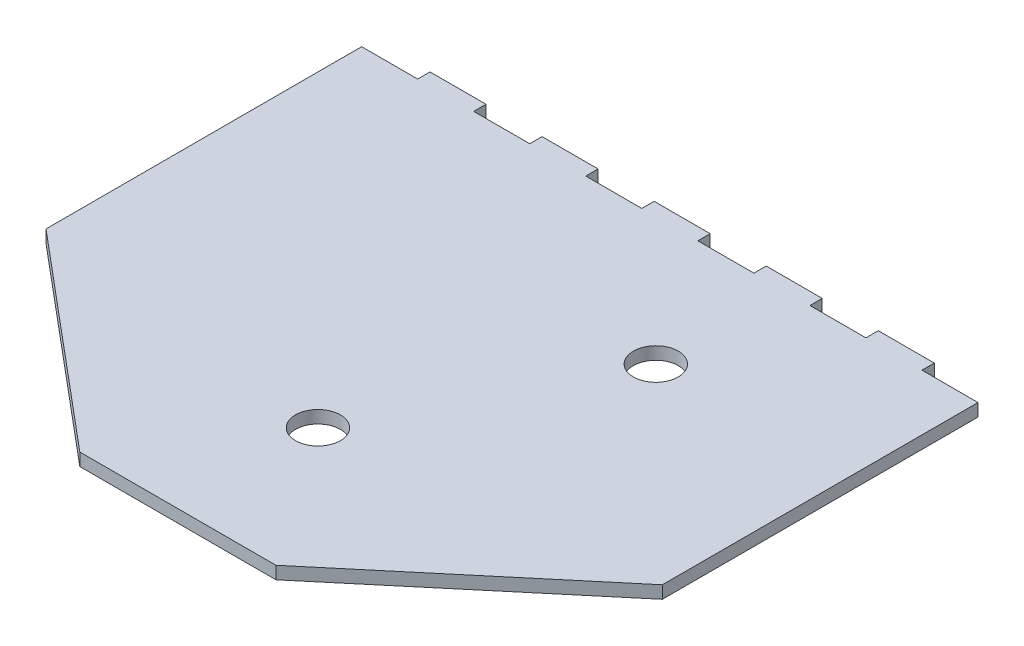
SolidWorks part; units mm, degrees
ref_plane "Front Plane" through (0, 0, 0) normal (0, 0, 1) x (1, 0, 0)
ref_plane "Top Plane" through (0, 0, 0) normal (0, 1, 0) x (1, 0, 0)
ref_plane "Right Plane" through (0, 0, 0) normal (1, 0, 0) x (0, 0, -1)
sketch "Sketch2" plane through (0, 0, 0) normal (0, 1, 0) x (1, 0, 0)
  line L3 (110, 90) -> (-110, 90)
  line L4 (110, 90) -> (110, -90)
  line L5 (110, -90) -> (-110, -90)
  line L6 (-110, 90) -> (-110, -90)
  line L7 (110, 90) -> (-110, -90) construction
  line L8 (110, -90) -> (-110, 90) construction
  point P0 (0, 0)
  dimension "D1" = 220
  dimension "D2" = 180
extrude "Boss-Extrude1" add sketch "Sketch2" along normal blind 4.5
chamfer "Chamfer1" distance 75 angle 40 2 edges at (-110, 2.25, 90) (110, 2.25, 90)
sketch "Sketch3" plane through (0, 4.5, 0) normal (0, 1, 0) x (1, 0, 0)
  line L0 (0, 90) -> (0, -40) construction
  line L1 (110, 90) -> (-110, 90) construction
  line L2 (0, -40) -> (40.6, -40) construction
  line L3 (40.6, -40) -> (40.6, 40) construction
  circle A0 centre (0, -40) radius 8
  circle A1 centre (40.6, 40) radius 8
  dimension "D2" = 16
  dimension "D5" = 16
  dimension "D1" = 130
  dimension "D3" = 80
  dimension "D4" = 40.6
extrude "Cut-Extrude1" cut sketch "Sketch3" against normal through all
sketch "Sketch4" plane through (0, 0, 0) normal (0, -1, 0) x (1, 0, 0)
  line L0 (110, 27.0675) -> (110, -90) construction
  line L1 (110, -90) -> (90, -90)
  line L2 (110, -90) -> (110, -85.6)
  line L3 (110, -85.6) -> (90, -85.6)
  line L4 (90, -90) -> (90, -85.6)
  line L5 (110, -90) -> (90, -85.6) construction
  line L6 (110, -85.6) -> (90, -90) construction
  line L7 (0, -90) -> (0, 0) construction
  line L8 (70, -90) -> (50, -90)
  line L9 (70, -90) -> (70, -85.6)
  line L10 (70, -85.6) -> (50, -85.6)
  line L11 (50, -90) -> (50, -85.6)
  line L12 (70, -90) -> (50, -85.6) construction
  line L13 (70, -85.6) -> (50, -90) construction
  line L14 (30, -90) -> (10, -90)
  line L15 (30, -90) -> (30, -85.6)
  line L16 (30, -85.6) -> (10, -85.6)
  line L17 (10, -90) -> (10, -85.6)
  line L18 (30, -90) -> (10, -85.6) construction
  line L19 (30, -85.6) -> (10, -90) construction
  line L20 (-30, -85.6) -> (-10, -90) construction
  line L21 (-30, -90) -> (-10, -85.6) construction
  line L22 (-70, -85.6) -> (-50, -90) construction
  line L23 (-70, -90) -> (-50, -85.6) construction
  line L24 (-110, -85.6) -> (-90, -90) construction
  line L25 (-110, -90) -> (-90, -85.6) construction
  line L26 (-10, -90) -> (-10, -85.6)
  line L27 (-30, -85.6) -> (-10, -85.6)
  line L28 (-30, -90) -> (-30, -85.6)
  line L29 (-30, -90) -> (-10, -90)
  line L30 (-50, -90) -> (-50, -85.6)
  line L31 (-70, -85.6) -> (-50, -85.6)
  line L32 (-70, -90) -> (-70, -85.6)
  line L33 (-70, -90) -> (-50, -90)
  line L34 (-90, -90) -> (-90, -85.6)
  line L35 (-110, -85.6) -> (-90, -85.6)
  line L36 (-110, -90) -> (-110, -85.6)
  line L37 (-110, -90) -> (-90, -90)
  line L38 (0, -90) -> (110, -90) construction
  point P4 (100, -87.8)
  point P29 (-100, -87.8)
  dimension "D1" = 4.4
  dimension "D2" = 20
  dimension "D3" = 3
  dimension "D4" = 90
  dimension "D5" = 20
extrude "Cut-Extrude2" cut sketch "Sketch4" against normal through all
